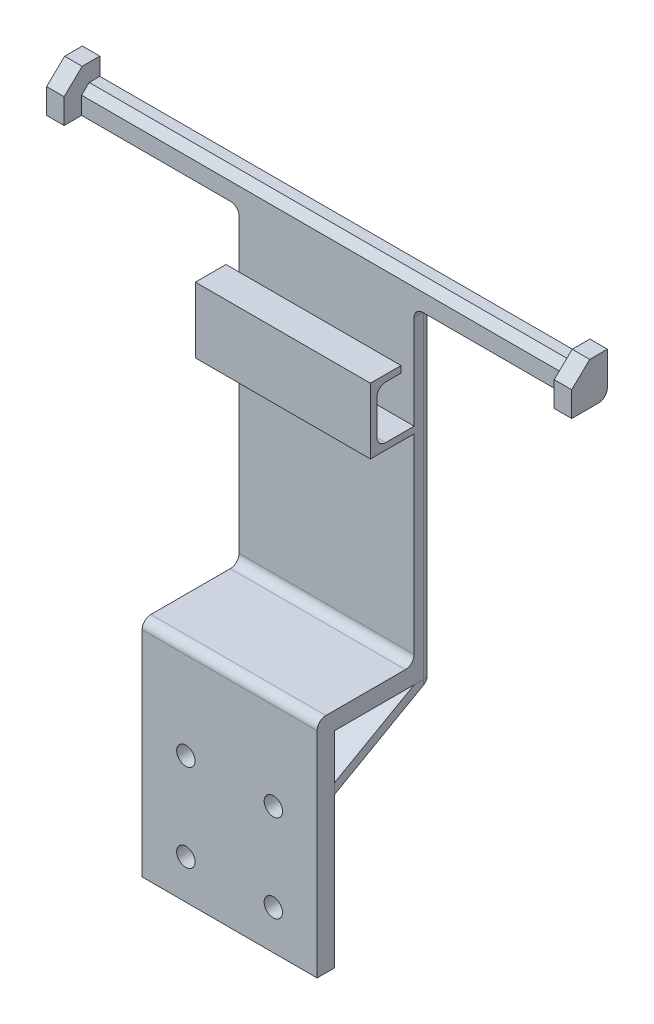
SolidWorks part; units mm, degrees
ref_plane "前视基准面" through (0, 0, 0) normal (0, 0, 1) x (1, 0, 0)
ref_plane "上视基准面" through (0, 0, 0) normal (0, 1, 0) x (1, 0, 0)
ref_plane "右视基准面" through (0, 0, 0) normal (1, 0, 0) x (0, 0, -1)
sketch "草图1" plane through (0, 0, 0) normal (0, 0, 1) x (1, 0, 0)
  line L0 (0, 0) -> (0, 10.35) construction
  line L1 (0, 0) -> (9.9931, 0) construction
  line L2 (20, 19) -> (-20, 19)
  line L3 (-20, 19) -> (-20, -16)
  line L4 (-20, -16) -> (20, -16)
  line L5 (0, 0) -> (-9.9931, 0) construction
  line L6 (20, 19) -> (20, -16)
  circle A0 centre (-10, 13) radius 2.1
  circle A1 centre (-10, -7) radius 2.1
  circle A2 centre (10, -7) radius 2.1
  circle A3 centre (10, 13) radius 2.1
  point P20 (0, -16)
  point P21 (0, 19)
  dimension "D1" = 4.2
  dimension "D3" = 4.2
  dimension "D2" = 35
  dimension "D4" = 13
  dimension "D5" = 20
  dimension "D6" = 19
  dimension "D7" = 20
  dimension "D8" = 10
  dimension "D9" = 10
extrude "凸台-拉伸1" add sketch "草图1" along normal blind 4
sketch "草图3" plane through (20, 0, 0) normal (1, 0, 0) x (0, 0, -1)
  line L0 (-4, 23.011) -> (-4, 19)
  line L1 (-4, 19) -> (0, 19) construction
  line L2 (0, 19) -> (22.3396, 25.6956)
  line L4 (-4, 19) -> (0, 19)
  line L7 (-4, 23.011) -> (0, 23.011)
  line L8 (22.3396, 25.6956) -> (22.3396, 54.3568)
  line L9 (0, 23.011) -> (18.1773, 28.4591)
  line L10 (22.3396, 54.3568) -> (18.1773, 54.3568)
  line L11 (18.1773, 54.3568) -> (18.1773, 28.4591)
  dimension "D1" = 4.011
  dimension "D4" = 4
extrude "凸台-拉伸2" add sketch "草图3" against normal up to surface (40 mm away) up to face at (-20, 1.5, 2)
sketch "草图4" plane through (0, 54.3568, 0) normal (0, 1, 0) x (1, 0, 0)
  line L0 (-20, 22.3396) -> (20, 22.3396)
  line L1 (20, 22.3396) -> (20, 18.1773)
  line L2 (20, 18.1773) -> (-20, 18.1773)
  line L3 (-20, 18.1773) -> (-20, 22.3396)
extrude "凸台-拉伸3" add sketch "草图4" along normal blind 56.94
sketch "草图5" plane through (20, 0, 0) normal (1, 0, 0) x (0, 0, -1)
  line L0 (19.9073, 111.2968) -> (18.1773, 109.6368)
  line L1 (18.1773, 111.2968) -> (22.3396, 111.2968) construction
  line L2 (18.1773, 111.2968) -> (18.1773, 28.4591) construction
  line L3 (18.1773, 109.6368) -> (18.1773, 111.2968)
  line L4 (18.1773, 111.2968) -> (19.9073, 111.2968)
  dimension "D1" = 1.73
  dimension "D2" = 1.66
extrude "切除-拉伸1" cut sketch "草图5" against normal through all
ref_plane "基准面4" through (0, 0, 0) normal (1, 0, 0) x (0, 0, -1)
sketch "草图6" plane through (0, 0, 0) normal (1, 0, 0) x (0, 0, -1)
  line L0 (19.9073, 111.2968) -> (22.3396, 111.2968) construction
  line L1 (18.1773, 109.6368) -> (19.9073, 111.2968) construction
  line L2 (19.9073, 111.2968) -> (22.3396, 111.2968)
  line L3 (18.1773, 109.6368) -> (19.9073, 111.2968)
  line L4 (22.3396, 111.2968) -> (22.3396, 105.6368)
  line L5 (22.3396, 25.6956) -> (22.3396, 111.2968) construction
  line L6 (22.3396, 105.6368) -> (18.1773, 105.6368)
  line L7 (18.1773, 109.6368) -> (18.1773, 28.4591) construction
  line L8 (18.1773, 105.6368) -> (18.1773, 109.6368)
  dimension "D1" = 4
extrude "凸台-拉伸4" add sketch "草图6" along normal mid plane 120
sketch "草图7" plane through (60, 0, 0) normal (1, 0, 0) x (0, 0, -1)
  line L3 (22.3396, 115.2968) -> (22.3396, 105.6368)
  line L4 (22.3396, 105.6368) -> (14.1773, 105.6368)
  line L6 (22.3396, 115.2968) -> (18.2987, 115.2968)
  line L7 (18.2987, 115.2968) -> (14.1773, 111.3423)
  line L8 (14.1773, 111.3423) -> (14.1773, 105.6368)
  line L9 (22.3396, 115.2968) -> (18.2987, 115.2968)
  line L10 (18.2987, 115.2968) -> (14.1773, 111.3423)
  line L11 (14.1773, 111.3423) -> (14.1773, 105.6368)
  dimension "D1" = 4
extrude "凸台-拉伸5" add sketch "草图7" against normal blind 4
sketch "草图9" plane through (-60, 0, 0) normal (-1, 0, 0) x (0, 0, 1)
  line L3 (-22.3396, 115.2968) -> (-22.3396, 105.6368)
  line L4 (-22.3396, 105.6368) -> (-14.1773, 105.6368)
  line L6 (-14.1773, 111.3423) -> (-14.1773, 105.6368)
  line L7 (-18.2987, 115.2968) -> (-14.1773, 111.3423)
  line L8 (-22.3396, 115.2968) -> (-18.2987, 115.2968)
  line L9 (-14.1773, 111.3423) -> (-14.1773, 105.6368)
  line L10 (-18.2987, 115.2968) -> (-14.1773, 111.3423)
  line L11 (-22.3396, 115.2968) -> (-18.2987, 115.2968)
  dimension "D1" = 4
extrude "凸台-拉伸6" add sketch "草图9" against normal blind 4
sketch "草图10" plane through (0, 0, -18.1773) normal (0, 0, 1) x (1, 0, 0)
  line L0 (-20, 95.6368) -> (-20, 80.6368)
  line L1 (-20, 28.4591) -> (-20, 105.6368) construction
  line L2 (-20, 80.6368) -> (20, 80.6368)
  line L3 (20, 105.6368) -> (20, 28.4591) construction
  line L4 (20, 80.6368) -> (20, 95.6368)
  line L5 (20, 95.6368) -> (-20, 95.6368)
  line L6 (-20, 105.6368) -> (-56, 105.6368) construction
  dimension "D1" = 15
  dimension "D2" = 10
extrude "凸台-拉伸7" add sketch "草图10" along normal blind 10
sketch "草图11" plane through (-20, 0, 0) normal (-1, 0, 0) x (0, 0, 1)
  line L3 (-18.1773, 94.1368) -> (-18.1773, 82.1368)
  line L6 (-18.1773, 82.1368) -> (-9.6773, 82.1368)
  line L7 (-9.6773, 82.1368) -> (-9.6773, 94.1368)
  line L8 (-9.6773, 94.1368) -> (-18.1773, 94.1368)
  line L9 (-18.1773, 82.1368) -> (-9.6773, 82.1368)
  line L10 (-9.6773, 82.1368) -> (-9.6773, 94.1368)
  line L11 (-9.6773, 94.1368) -> (-18.1773, 94.1368)
  dimension "D1" = 1.5
extrude "切除-拉伸2" cut sketch "草图11" against normal through all
sketch "草图12" plane through (-20, 0, 0) normal (-1, 0, 0) x (0, 0, 1)
  line L0 (-18.1773, 95.6368) -> (-18.1773, 94.1368)
  line L1 (-18.1773, 94.1368) -> (-15.1773, 94.1368)
  line L2 (-9.6773, 94.1368) -> (-18.1773, 94.1368) construction
  line L3 (-15.1773, 94.1368) -> (-15.1773, 95.6368)
  line L4 (-8.1773, 95.6368) -> (-18.1773, 95.6368) construction
  line L5 (-15.1773, 95.6368) -> (-18.1773, 95.6368)
  dimension "D1" = 3
extrude "切除-拉伸3" cut sketch "草图12" against normal through all
sketch "草图13" plane through (20, 0, 0) normal (1, 0, 0) x (0, 0, -1)
  line L0 (0, 23.011) -> (0, 19)
  line L1 (18.1773, 28.4591) -> (18.1773, 24.4481)
  line L2 (0, 19) -> (22.3396, 25.6956) construction
  line L3 (18.1773, 24.4481) -> (18.1773, 19)
  line L4 (18.1773, 19) -> (0, 19)
  line L5 (18.1773, 28.4591) -> (0, 28.4591)
  line L6 (0, 28.4591) -> (0, 23.011)
extrude "切除-拉伸4" cut sketch "草图13" against normal through all
sketch "草图14" plane through (20, 0, 0) normal (1, 0, 0) x (0, 0, -1)
  line L0 (22.3396, 25.6956) -> (18.1773, 25.6956)
  line L1 (18.1773, 80.6368) -> (18.1773, 24.4481) construction
  line L2 (18.1773, 25.6956) -> (18.1773, 24.4481)
  line L3 (18.1773, 24.4481) -> (22.3396, 25.6956)
extrude "切除-拉伸5" cut sketch "草图14" against normal through all
sketch "草图18" plane through (20, 0, 0) normal (1, 0, 0) x (0, 0, -1)
  line L0 (-4, 23.011) -> (-4, 34.951)
  line L1 (-4, 34.951) -> (22.3396, 34.951)
  line L2 (22.3396, 25.6956) -> (22.3396, 105.6368) construction
  line L3 (0, 23.011) -> (0, 30.951)
  line L4 (0, 30.951) -> (22.3396, 30.951)
  line L5 (22.3396, 30.951) -> (22.3396, 34.951)
  line L8 (-4, 23.011) -> (0, 23.011)
  dimension "D1" = 4
extrude "凸台-拉伸10" add sketch "草图18" against normal blind 40
sketch "草图19" plane through (20, 0, 0) normal (1, 0, 0) x (0, 0, -1)
  line L0 (18.1773, 30.951) -> (22.3396, 30.951)
  line L1 (22.3396, 25.6956) -> (22.3396, 105.6368) construction
  line L2 (22.3396, 30.951) -> (22.3396, 25.6956)
  line L3 (22.3396, 25.6956) -> (18.1773, 25.6956)
  line L4 (18.1773, 25.6956) -> (18.1773, 30.951)
extrude "切除-拉伸6" cut sketch "草图19" against normal through all
sketch "草图20" plane through (20, 0, 0) normal (1, 0, 0) x (0, 0, -1)
  line L0 (22.3396, 30.951) -> (0, 18.3251)
  line L1 (0, -16) -> (0, 30.951) construction
  line L3 (0, 30.951) -> (22.3396, 30.951) construction
  line L4 (18.1773, 30.951) -> (0, 20.6776)
  line L5 (18.1773, 30.951) -> (22.3396, 30.951)
  line L6 (0, 20.6776) -> (0, 18.3251)
  point P8 (18.1773, 30.951)
extrude "凸台-拉伸11" add sketch "草图20" against normal blind 40 separate body
fillet "圆角2" radius 2 1 edges at (0, 34.951, 4)
fillet "圆角3" radius 2 1 edges at (0, 34.951, -18.1773)
fillet "圆角4" radius 2 2 edges at (-20, 105.6368, -20.2585) (20, 105.6368, -20.2585)
fillet "圆角5" radius 2 6 edges at (-20, 67.2939, -22.3396) (-20.5858, 105.051, -22.3396) (20, 67.2939, -22.3396) (20.5858, 105.051, -22.3396) (-41, 105.6368, -22.3396) (41, 105.6368, -22.3396)
sketch "草图21" plane through (0, 30.951, 0) normal (0, 1, 0) x (1, 0, 0)
  line L5 (-20, 22.3396) -> (-20, 20.3396)
  line L6 (-20, 22.3396) -> (-18, 22.3396)
  line L7 (20, 22.3396) -> (18, 22.3396)
  line L8 (20, 20.3396) -> (20, 22.3396)
  arc A0 (-18, 22.3396) -> (-20, 20.3396) centre (-18, 20.3396) ccw construction
  arc A1 (-18, 22.3396) -> (-20, 20.3396) centre (-18, 20.3396) ccw
  arc A2 (20, 20.3396) -> (18, 22.3396) centre (18, 20.3396) ccw construction
  arc A3 (20, 20.3396) -> (18, 22.3396) centre (18, 20.3396) ccw
extrude "切除-拉伸7" cut sketch "草图21" against normal through all
fillet "圆角6" radius 2 2 edges at (0, 94.1368, -9.6773) (0, 82.1368, -9.6773)
